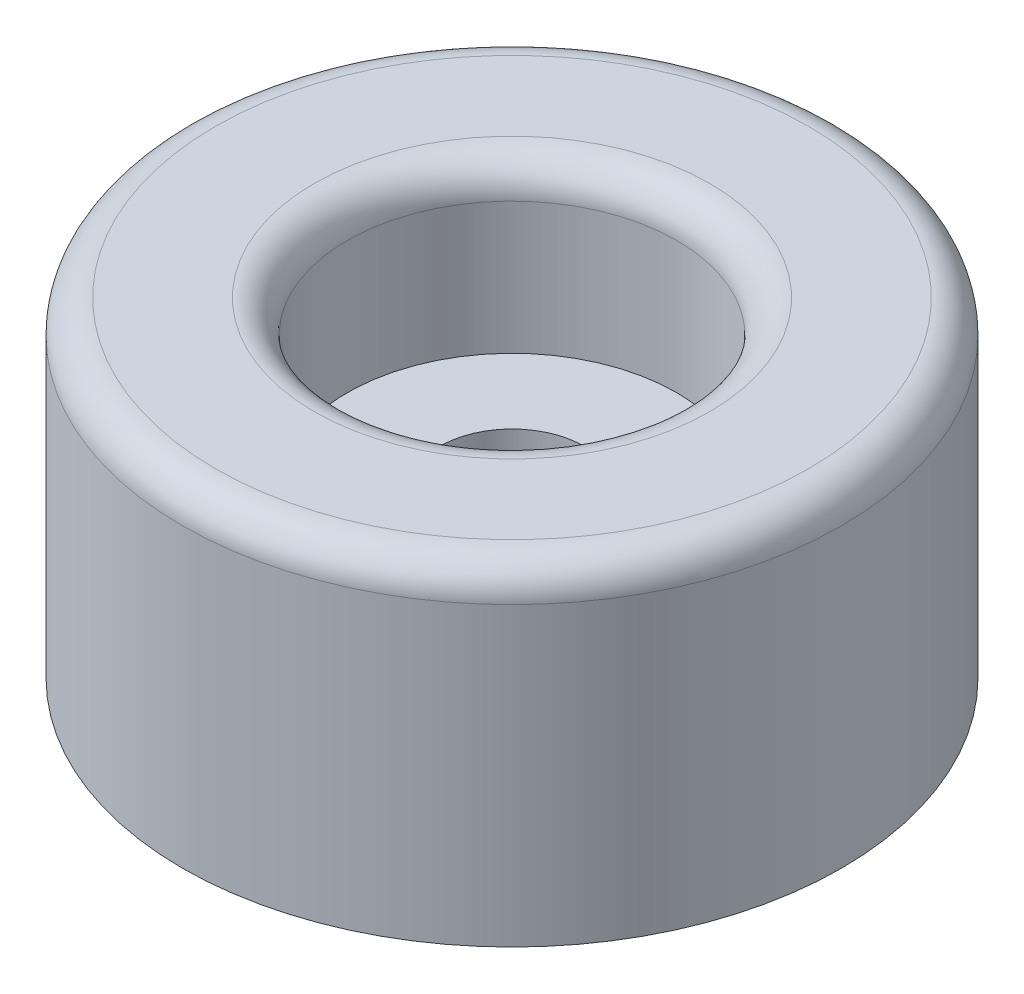
SolidWorks part; units mm, degrees
material "Rubber"
ref_plane "Front" through (0, 0, 0) normal (0, 0, 1) x (1, 0, 0)
ref_plane "Top" through (0, 0, 0) normal (0, 1, 0) x (1, 0, 0)
ref_plane "Right" through (0, 0, 0) normal (1, 0, 0) x (0, 0, -1)
sketch "Sketch1" plane through (0, 0, 0) normal (0, 1, 0) x (1, 0, 0)
  circle A0 centre (0, 0) radius 12.7
  dimension "D1" = 25.4
extrude "Boss-Extrude1" add sketch "Sketch1" along normal blind 12.7
sketch "Sketch2" plane through (0, 12.7, 0) normal (0, 1, 0) x (1, 0, 0)
  circle A0 centre (0, 0) radius 6.35
  dimension "D1" = 12.7
extrude "Cut-Extrude1" cut sketch "Sketch2" against normal blind 6.35
sketch "Sketch3" plane through (0, 6.35, 0) normal (0, 1, 0) x (1, 0, 0)
  circle A0 centre (0, 0) radius 2.7781
  dimension "D1" = 5.5562
extrude "Cut-Extrude2" cut sketch "Sketch3" against normal through all
fillet "Fillet1" radius 1.27 2 edges at (0, 12.7, 6.35) (0, 12.7, 12.7)
